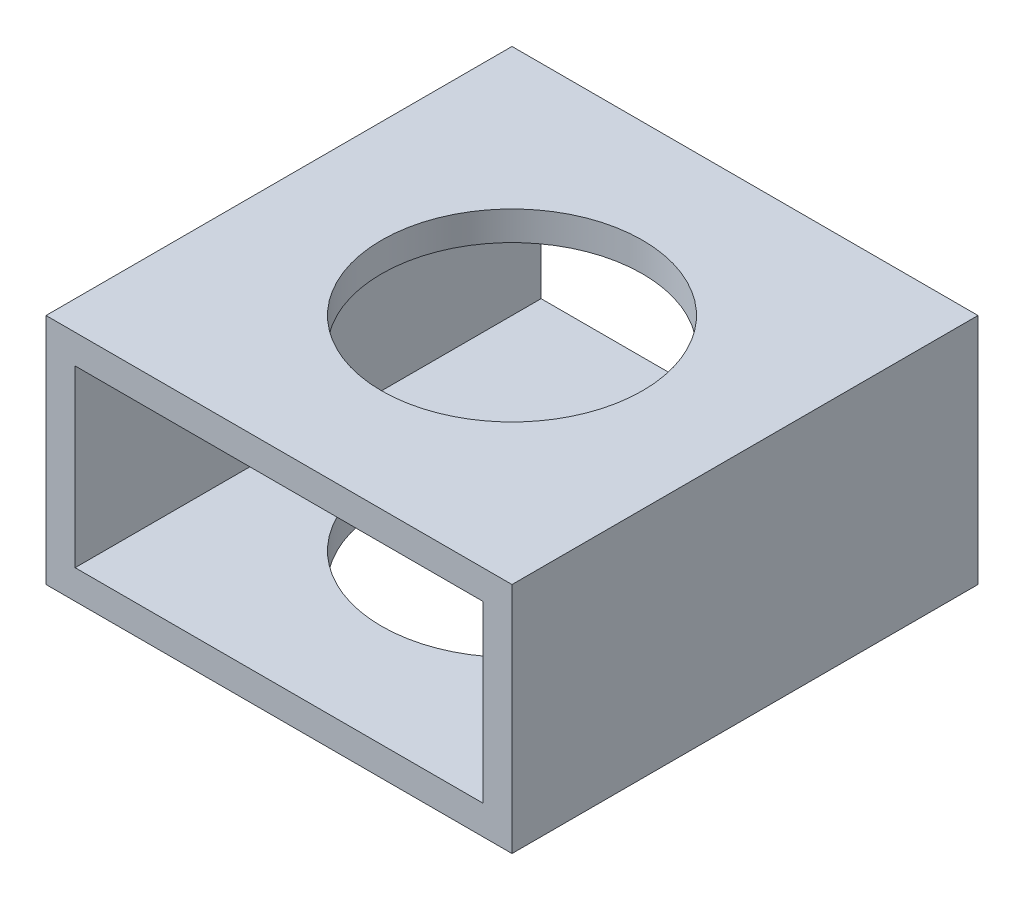
SolidWorks part; units mm, degrees
ref_plane "Front Plane" through (0, 0, 0) normal (0, 0, 1) x (1, 0, 0)
ref_plane "Top Plane" through (0, 0, 0) normal (0, 1, 0) x (1, 0, 0)
ref_plane "Right Plane" through (0, 0, 0) normal (1, 0, 0) x (0, 0, -1)
sketch "Sketch1" plane through (0, 0, 0) normal (0, 0, 1) x (1, 0, 0)
  line L0 (3.175, 3.175) -> (3.175, 22.225)
  line L1 (0, 0) -> (50.8, 0)
  line L2 (0, 0) -> (0, 25.4)
  line L3 (0, 25.4) -> (50.8, 25.4)
  line L4 (50.8, 0) -> (50.8, 25.4)
  line L5 (3.175, 22.225) -> (47.625, 22.225)
  line L6 (47.625, 3.175) -> (47.625, 22.225)
  line L7 (3.175, 3.175) -> (47.625, 3.175)
  dimension "D1" = 50.8
  dimension "D2" = 25.4
  dimension "D3" = 3.175
extrude "Boss-Extrude1" add sketch "Sketch1" along normal blind 50.8
sketch "Sketch2" plane through (0, 25.4, 0) normal (0, 1, 0) x (1, 0, 0)
  line L0 (0, -50.8) -> (0, 0) construction
  line L2 (50.8, 0) -> (0, 0) construction
  circle A0 centre (25.4, -25.4) radius 14.224
  dimension "D1" = 28.448
  dimension "D2" = 25.4
  dimension "D3" = 25.4
extrude "Cut-Extrude1" cut sketch "Sketch2" against normal through all
